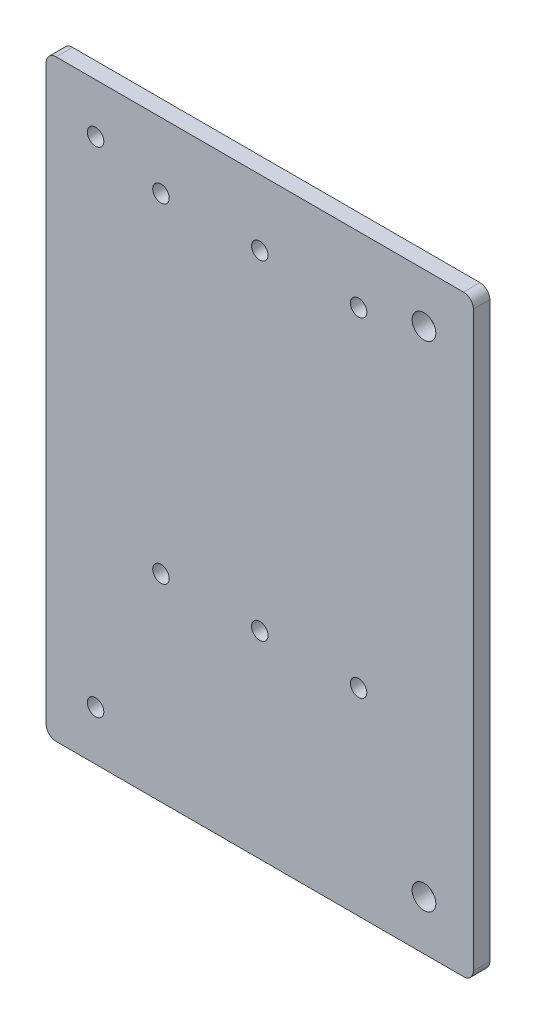
SolidWorks part; units mm, degrees
ref_plane "Płaszczyzna przednia" through (0, 0, 0) normal (0, 0, 1) x (1, 0, 0)
ref_plane "Płaszczyzna górna" through (0, 0, 0) normal (0, 1, 0) x (1, 0, 0)
ref_plane "Płaszczyzna prawa" through (0, 0, 0) normal (1, 0, 0) x (0, 0, -1)
sketch "Sketch1" plane through (0, 0, 0) normal (0, 0, 1) x (1, 0, 0)
  line L0 (64.85, -11.9796) -> (64.85, 45.4278) construction
  line L1 (0, 0) -> (129.7, 0)
  line L2 (0, 0) -> (0, 180)
  line L3 (0, 180) -> (129.7, 180)
  line L4 (129.7, 0) -> (129.7, 180)
  line L5 (-13.2189, 110) -> (166.9359, 110) construction
  line L6 (166.9359, 150) -> (-13.2189, 150) construction
  line L7 (166.9359, 70) -> (-17.016, 70) construction
  line L8 (-17.016, 160) -> (166.9359, 160) construction
  line L9 (-13.2189, 60) -> (174.7412, 60) construction
  circle A0 centre (15, 15) radius 2.5
  circle A1 centre (15, 165) radius 2.5
  circle A2 centre (114.7, 165) radius 3.6
  circle A3 centre (114.7, 15) radius 3.6
  circle A4 centre (34.85, 160) radius 2.5
  circle A5 centre (64.85, 160) radius 2.5
  circle A6 centre (94.85, 160) radius 2.5
  circle A7 centre (34.85, 60) radius 2.5
  circle A8 centre (64.85, 60) radius 2.5
  circle A9 centre (94.85, 60) radius 2.5
  point P18 (64.85, 0)
  dimension "D1" = 5
  dimension "D2" = 5
  dimension "D3" = 7.2
  dimension "D4" = 7.2
  dimension "D19" = 5
  dimension "D5" = 99.7
  dimension "D6" = 150
  dimension "D7" = 15
  dimension "D8" = 15
  dimension "D9" = 15
  dimension "D10" = 70
  dimension "D11" = 40
  dimension "D12" = 40
  dimension "D13" = 10
  dimension "D14" = 10
  dimension "D15" = 30
  dimension "D16" = 30
  dimension "D17" = 30
  dimension "D18" = 30
extrude "Boss-Extrude1" add sketch "Sketch1" along normal blind 5
fillet "Fillet1" radius 3 4 edges at (0, 0, 2.5) (129.7, 0, 2.5) (0, 180, 2.5) (129.7, 180, 2.5)
